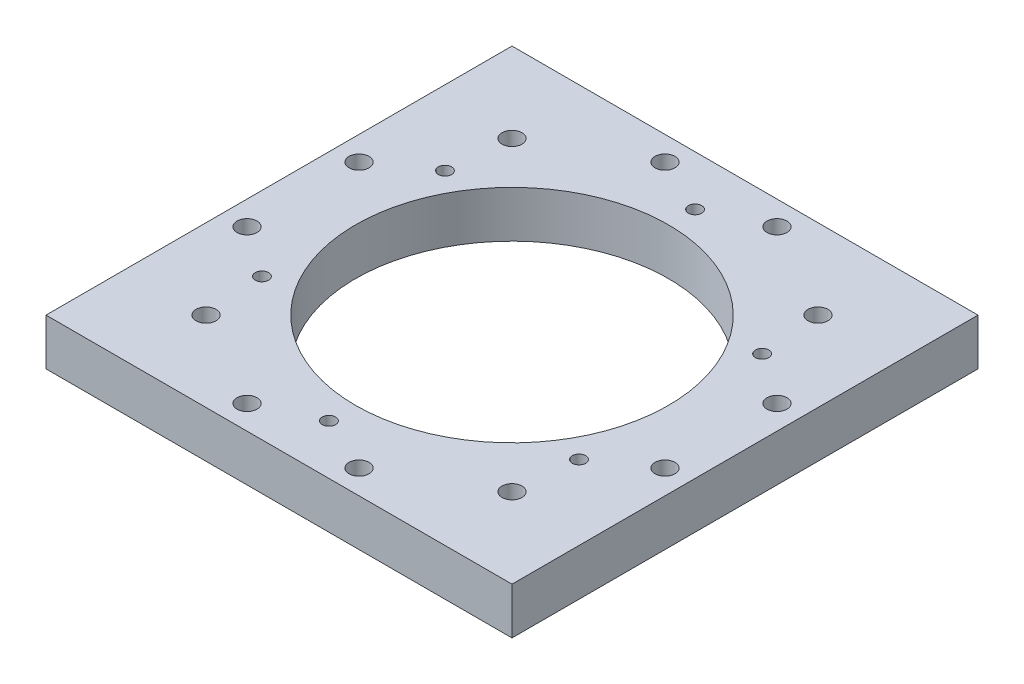
SolidWorks part; units mm, degrees
ref_plane "Front Plane" through (0, 0, 0) normal (0, 0, 1) x (1, 0, 0)
ref_plane "Top Plane" through (0, 0, 0) normal (0, 1, 0) x (1, 0, 0)
ref_plane "Right Plane" through (0, 0, 0) normal (1, 0, 0) x (0, 0, -1)
sketch "Sketch1" plane through (0, 0, 0) normal (0, 1, 0) x (1, 0, 0)
  line L0 (-53.2191, 0) -> (0, 0) construction
  line L1 (0, 0) -> (-55.1529, -14.7782) construction
  line L2 (-35, 35) -> (35, 35)
  line L3 (-35, 35) -> (-35, -35)
  line L4 (35, 35) -> (35, -35)
  line L5 (-35, -35) -> (35, -35)
  circle A0 centre (0, 0) radius 35 construction
  circle A1 centre (0, 0) radius 27.5 construction
  circle A2 centre (0, 0) radius 23.5
  circle A3 centre (0, 27.5) radius 1
  circle A4 centre (23.8157, 13.75) radius 1
  circle A5 centre (23.8157, -13.75) radius 1
  circle A6 centre (0, -27.5) radius 1
  circle A7 centre (-23.8157, -13.75) radius 1
  circle A8 centre (-23.8157, 13.75) radius 1
  circle A9 centre (0, 0) radius 32.5 construction
  circle A10 centre (-31.3926, -8.4116) radius 1.5
  circle A11 centre (-31.3926, 8.4116) radius 1.5
  circle A12 centre (-22.981, 22.981) radius 1.5
  circle A13 centre (-8.4116, 31.3926) radius 1.5
  circle A14 centre (8.4116, 31.3926) radius 1.5
  circle A15 centre (22.981, 22.981) radius 1.5
  circle A16 centre (31.3926, 8.4116) radius 1.5
  circle A17 centre (31.3926, -8.4116) radius 1.5
  circle A18 centre (22.981, -22.981) radius 1.5
  circle A19 centre (8.4116, -31.3926) radius 1.5
  circle A20 centre (-8.4116, -31.3926) radius 1.5
  circle A21 centre (-22.981, -22.981) radius 1.5
  point P19 (0, 0)
  point P47 (0, 0)
  dimension "D1" = 70
  dimension "D2" = 47
  dimension "D3" = 55
  dimension "D4" = 2
  dimension "D7" = 65
  dimension "D8" = 3
  dimension "D6" = 15
  dimension "D5" = 6
  dimension "D9" = 12
extrude "Boss-Extrude1" add sketch "Sketch1" along normal blind 7
